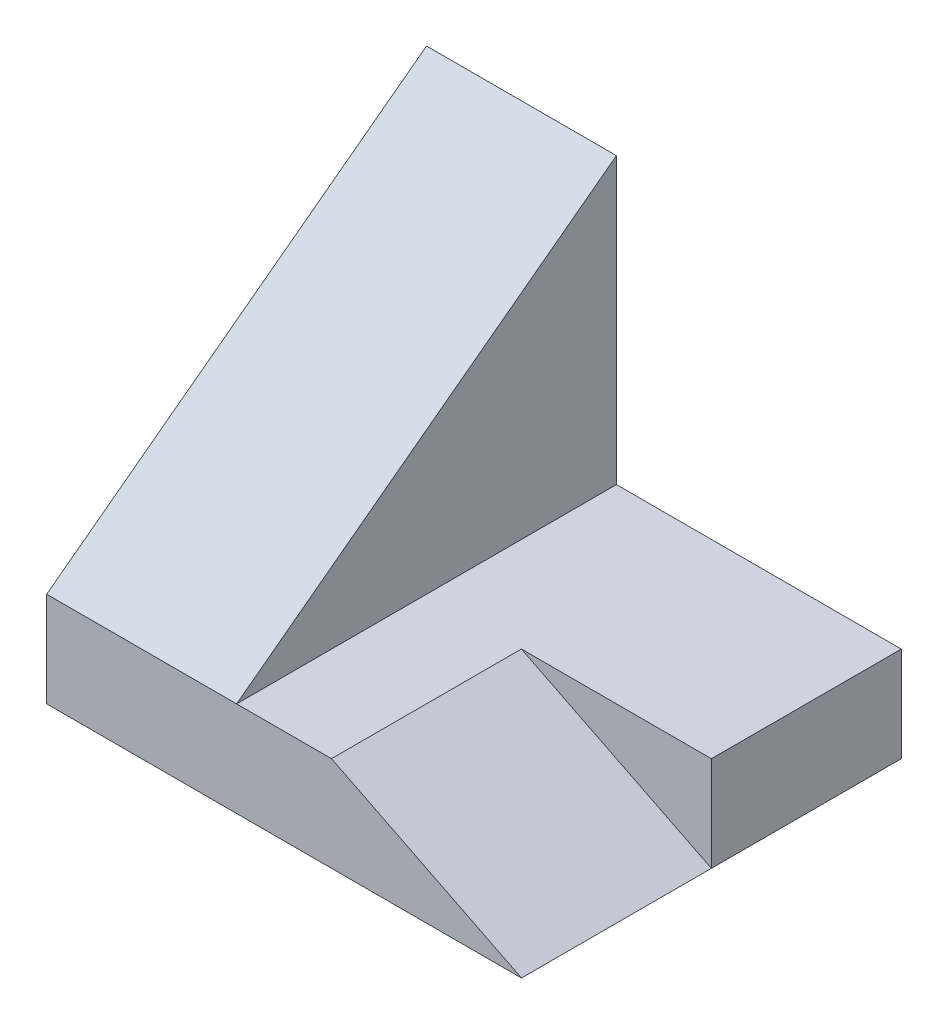
SolidWorks part; units mm, degrees
ref_plane "Front Plane" through (0, 0, 0) normal (0, 0, 1) x (1, 0, 0)
ref_plane "Top Plane" through (0, 0, 0) normal (0, 1, 0) x (1, 0, 0)
ref_plane "Right Plane" through (0, 0, 0) normal (1, 0, 0) x (0, 0, -1)
sketch "Sketch16" plane through (0, 0, 0) normal (0, 1, 0) x (1, 0, 0)
  line L5 (0, 0) -> (50, 0)
  line L6 (0, 0) -> (0, 40)
  line L7 (0, 40) -> (50, 40)
  line L8 (50, 0) -> (50, 40)
  dimension "D1" = 50
  dimension "D2" = 40
extrude "Boss-Extrude3" add sketch "Sketch16" along normal blind 10
sketch "Sketch20" plane through (0, 0, 0) normal (0, 0, 1) x (1, 0, 0)
  line L0 (50, 10) -> (29.992, 10)
  line L1 (0, 10) -> (50, 10) construction
  line L2 (29.992, 10) -> (50, 0)
  line L3 (50, 0) -> (50, 10)
extrude "Cut-Extrude10" cut sketch "Sketch20" against normal blind 20
sketch "Sketch21" plane through (0, 10, 0) normal (0, 1, 0) x (1, 0, 0)
  line L0 (50, 40) -> (0, 40) construction
  line L1 (0, 0) -> (20.0003, 0)
  line L2 (0, 0) -> (0, 40)
  line L3 (0, 40) -> (20.0003, 40)
  line L4 (20.0003, 0) -> (20.0003, 40)
extrude "Boss-Extrude4" add sketch "Sketch21" along normal blind 30
sketch "Sketch22" plane through (20.0003, 0, 0) normal (1, 0, 0) x (0, 0, -1)
  line L0 (40, 40) -> (0, 40)
  line L1 (0, 40) -> (0, 10)
  line L2 (0, 10) -> (40, 40)
extrude "Cut-Extrude12" cut sketch "Sketch22" against normal blind 21
